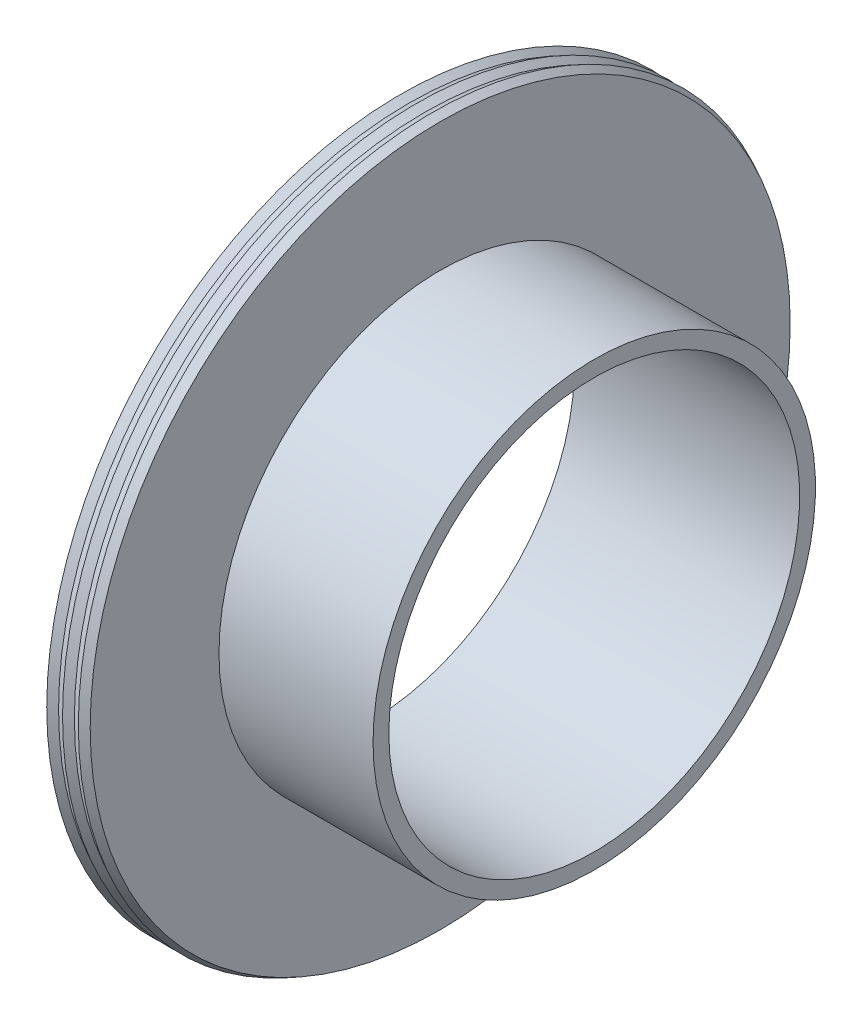
SolidWorks part; units mm, degrees
ref_plane "前视基准面" through (0, 0, 0) normal (0, 0, 1) x (1, 0, 0)
ref_plane "上视基准面" through (0, 0, 0) normal (0, 1, 0) x (1, 0, 0)
ref_plane "右视基准面" through (0, 0, 0) normal (1, 0, 0) x (0, 0, -1)
other "Configuration Table"
sketch "草图1" plane through (0, 0, 0) normal (0, 0, 1) x (1, 0, 0)
  line L0 (-59.6593, 0) -> (89.3294, 0) construction
  line L1 (0, 0) -> (0, 26)
  line L2 (0, 26) -> (28.5, 26)
  line L3 (28.5, 26) -> (28.5, 28)
  line L4 (28.5, 28) -> (0, 28)
  line L5 (0, 28) -> (0, 26)
  line L6 (0, 0) -> (0, 28)
  line L8 (4, 44.8) -> (9, 44.8)
  line L9 (9, 44.8) -> (9, 28)
  line L10 (9, 28) -> (4, 28)
  line L11 (4, 28) -> (4, 44.8)
  line L13 (4, 44.8) -> (5, 44.3)
  line L14 (5, 44.3) -> (6, 44.8)
  line L15 (6, 44.8) -> (7, 44.3)
  line L16 (7, 44.3) -> (8, 44.8)
  line L17 (8, 44.8) -> (9, 44.3)
  line L19 (9, 44.3) -> (10, 44.8) [skipped]
  dimension "D1" = 26
  dimension "D2" = 2
  dimension "D3" = 28.5
  dimension "D5" = 5
  dimension "D6" = 16.8
  dimension "D9" = 1
  dimension "D10" = 3
revolve "旋转1" add sketch "草图1" angle 360 about L0
